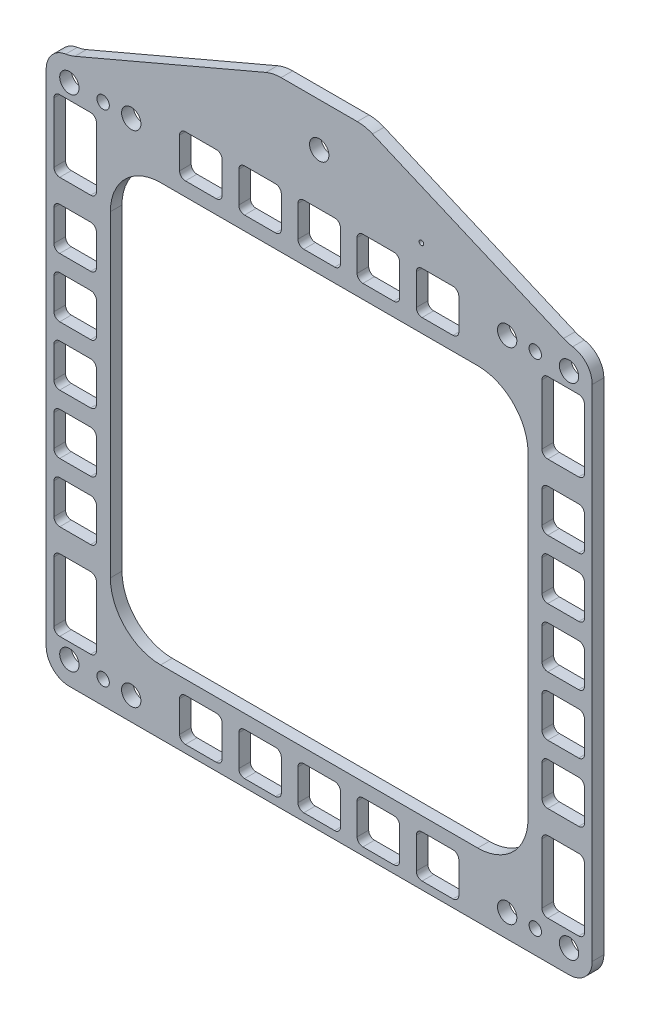
SolidWorks part; units mm, degrees
ref_plane "Front Plane" through (0, 0, 0) normal (0, 0, 1) x (1, 0, 0)
ref_plane "Top Plane" through (0, 0, 0) normal (0, 1, 0) x (1, 0, 0)
ref_plane "Right Plane" through (0, 0, 0) normal (1, 0, 0) x (0, 0, -1)
sketch "Sketch1" plane through (0, 0, 0) normal (0, 0, 1) x (1, 0, 0)
  point P0 (0, 54)
  point P1 (-54, 0)
  line B0 (-70.6, -64.6) -> (-70.6, 64.6)
  line B1 (-57.6, 43.65) -> (-57.6, 59.15)
  line B2 (-36.1, 67.1) -> (-36.1, 59.1)
  line B3 (-63.1825, 71.2052) -> (-13.7811, 92.2969)
  circle B4 centre (26.429, 74.25) radius 0.6
  circle B5 centre (0, 81.85) radius 2.5
  line B6 (-67.1, -60.65) -> (-59.1, -60.65)
  arc B7 (-68.6, -59.15) -> (-67.1, -60.65) centre (-67.1, -59.15) ccw
  line B8 (-68.6, -43.65) -> (-68.6, -59.15)
  arc B9 (-67.1, -42.15) -> (-68.6, -43.65) centre (-67.1, -43.65) ccw
  line B10 (-59.1, -42.15) -> (-67.1, -42.15)
  arc B11 (-57.6, -43.65) -> (-59.1, -42.15) centre (-59.1, -43.65) ccw
  line B12 (-57.6, -59.15) -> (-57.6, -43.65)
  arc B13 (-59.1, -60.65) -> (-57.6, -59.15) centre (-59.1, -59.15) ccw
  line B14 (67.1, -42.15) -> (59.1, -42.15)
  arc B15 (68.6, -43.65) -> (67.1, -42.15) centre (67.1, -43.65) ccw
  line B16 (68.6, -59.15) -> (68.6, -43.65)
  arc B17 (67.1, -60.65) -> (68.6, -59.15) centre (67.1, -59.15) ccw
  line B18 (59.1, -60.65) -> (67.1, -60.65)
  arc B19 (57.6, -59.15) -> (59.1, -60.65) centre (59.1, -59.15) ccw
  line B20 (57.6, -43.65) -> (57.6, -59.15)
  arc B21 (59.1, -42.15) -> (57.6, -43.65) centre (59.1, -43.65) ccw
  line B22 (67.1, 60.65) -> (59.1, 60.65)
  arc B23 (68.6, 59.15) -> (67.1, 60.65) centre (67.1, 59.15) ccw
  line B24 (68.6, 43.65) -> (68.6, 59.15)
  arc B25 (67.1, 42.15) -> (68.6, 43.65) centre (67.1, 43.65) ccw
  line B26 (59.1, 42.15) -> (67.1, 42.15)
  arc B27 (57.6, 43.65) -> (59.1, 42.15) centre (59.1, 43.65) ccw
  line B28 (57.6, 59.15) -> (57.6, 43.65)
  arc B29 (59.1, 60.65) -> (57.6, 59.15) centre (59.1, 59.15) ccw
  line B30 (-67.1, 42.15) -> (-59.1, 42.15)
  arc B31 (-68.6, 43.65) -> (-67.1, 42.15) centre (-67.1, 43.65) ccw
  line B32 (-68.6, 59.15) -> (-68.6, 43.65)
  arc B33 (-67.1, 60.65) -> (-68.6, 59.15) centre (-67.1, 59.15) ccw
  line B34 (-59.1, 60.65) -> (-67.1, 60.65)
  arc B35 (-57.6, 59.15) -> (-59.1, 60.65) centre (-59.1, 59.15) ccw
  arc B36 (-59.1, 42.15) -> (-57.6, 43.65) centre (-59.1, 43.65) ccw
  line B37 (68.6, 26.6) -> (68.6, 34.6)
  arc B38 (68.6, 34.6) -> (67.1, 36.1) centre (67.1, 34.6) ccw
  line B39 (67.1, 36.1) -> (59.1, 36.1)
  arc B40 (59.1, 36.1) -> (57.6, 34.6) centre (59.1, 34.6) ccw
  line B41 (57.6, 26.6) -> (57.6, 34.6)
  arc B42 (57.6, 26.6) -> (59.1, 25.1) centre (59.1, 26.6) ccw
  line B43 (67.1, 25.1) -> (59.1, 25.1)
  arc B44 (67.1, 25.1) -> (68.6, 26.6) centre (67.1, 26.6) ccw
  line B45 (68.6, 11.3) -> (68.6, 19.3)
  arc B46 (68.6, 19.3) -> (67.1, 20.8) centre (67.1, 19.3) ccw
  line B47 (67.1, 20.8) -> (59.1, 20.8)
  arc B48 (59.1, 20.8) -> (57.6, 19.3) centre (59.1, 19.3) ccw
  line B49 (57.6, 11.3) -> (57.6, 19.3)
  arc B50 (57.6, 11.3) -> (59.1, 9.8) centre (59.1, 11.3) ccw
  line B51 (67.1, 9.8) -> (59.1, 9.8)
  arc B52 (67.1, 9.8) -> (68.6, 11.3) centre (67.1, 11.3) ccw
  line B53 (68.6, -4) -> (68.6, 4)
  arc B54 (68.6, 4) -> (67.1, 5.5) centre (67.1, 4) ccw
  line B55 (67.1, 5.5) -> (59.1, 5.5)
  arc B56 (59.1, 5.5) -> (57.6, 4) centre (59.1, 4) ccw
  line B57 (57.6, -4) -> (57.6, 4)
  arc B58 (57.6, -4) -> (59.1, -5.5) centre (59.1, -4) ccw
  line B59 (67.1, -5.5) -> (59.1, -5.5)
  arc B60 (67.1, -5.5) -> (68.6, -4) centre (67.1, -4) ccw
  line B61 (68.6, -19.3) -> (68.6, -11.3)
  arc B62 (68.6, -11.3) -> (67.1, -9.8) centre (67.1, -11.3) ccw
  line B63 (67.1, -9.8) -> (59.1, -9.8)
  arc B64 (59.1, -9.8) -> (57.6, -11.3) centre (59.1, -11.3) ccw
  line B65 (57.6, -19.3) -> (57.6, -11.3)
  arc B66 (57.6, -19.3) -> (59.1, -20.8) centre (59.1, -19.3) ccw
  line B67 (67.1, -20.8) -> (59.1, -20.8)
  arc B68 (67.1, -20.8) -> (68.6, -19.3) centre (67.1, -19.3) ccw
  line B69 (68.6, -34.6) -> (68.6, -26.6)
  arc B70 (68.6, -26.6) -> (67.1, -25.1) centre (67.1, -26.6) ccw
  line B71 (67.1, -25.1) -> (59.1, -25.1)
  arc B72 (59.1, -25.1) -> (57.6, -26.6) centre (59.1, -26.6) ccw
  line B73 (57.6, -34.6) -> (57.6, -26.6)
  arc B74 (57.6, -34.6) -> (59.1, -36.1) centre (59.1, -34.6) ccw
  line B75 (67.1, -36.1) -> (59.1, -36.1)
  arc B76 (67.1, -36.1) -> (68.6, -34.6) centre (67.1, -34.6) ccw
  line B77 (26.6, -68.6) -> (34.6, -68.6)
  arc B78 (34.6, -68.6) -> (36.1, -67.1) centre (34.6, -67.1) ccw
  line B79 (36.1, -67.1) -> (36.1, -59.1)
  arc B80 (36.1, -59.1) -> (34.6, -57.6) centre (34.6, -59.1) ccw
  line B81 (26.6, -57.6) -> (34.6, -57.6)
  arc B82 (26.6, -57.6) -> (25.1, -59.1) centre (26.6, -59.1) ccw
  line B83 (25.1, -67.1) -> (25.1, -59.1)
  arc B84 (25.1, -67.1) -> (26.6, -68.6) centre (26.6, -67.1) ccw
  line B85 (11.3, -68.6) -> (19.3, -68.6)
  arc B86 (19.3, -68.6) -> (20.8, -67.1) centre (19.3, -67.1) ccw
  line B87 (20.8, -67.1) -> (20.8, -59.1)
  arc B88 (20.8, -59.1) -> (19.3, -57.6) centre (19.3, -59.1) ccw
  line B89 (11.3, -57.6) -> (19.3, -57.6)
  arc B90 (11.3, -57.6) -> (9.8, -59.1) centre (11.3, -59.1) ccw
  line B91 (9.8, -67.1) -> (9.8, -59.1)
  arc B92 (9.8, -67.1) -> (11.3, -68.6) centre (11.3, -67.1) ccw
  line B93 (-4, -68.6) -> (4, -68.6)
  arc B94 (4, -68.6) -> (5.5, -67.1) centre (4, -67.1) ccw
  line B95 (5.5, -67.1) -> (5.5, -59.1)
  arc B96 (5.5, -59.1) -> (4, -57.6) centre (4, -59.1) ccw
  line B97 (-4, -57.6) -> (4, -57.6)
  arc B98 (-4, -57.6) -> (-5.5, -59.1) centre (-4, -59.1) ccw
  line B99 (-5.5, -67.1) -> (-5.5, -59.1)
  arc B100 (-5.5, -67.1) -> (-4, -68.6) centre (-4, -67.1) ccw
  line B101 (-19.3, -68.6) -> (-11.3, -68.6)
  arc B102 (-11.3, -68.6) -> (-9.8, -67.1) centre (-11.3, -67.1) ccw
  line B103 (-9.8, -67.1) -> (-9.8, -59.1)
  arc B104 (-9.8, -59.1) -> (-11.3, -57.6) centre (-11.3, -59.1) ccw
  line B105 (-19.3, -57.6) -> (-11.3, -57.6)
  arc B106 (-19.3, -57.6) -> (-20.8, -59.1) centre (-19.3, -59.1) ccw
  line B107 (-20.8, -67.1) -> (-20.8, -59.1)
  arc B108 (-20.8, -67.1) -> (-19.3, -68.6) centre (-19.3, -67.1) ccw
  line B109 (-34.6, -68.6) -> (-26.6, -68.6)
  arc B110 (-26.6, -68.6) -> (-25.1, -67.1) centre (-26.6, -67.1) ccw
  line B111 (-25.1, -67.1) -> (-25.1, -59.1)
  arc B112 (-25.1, -59.1) -> (-26.6, -57.6) centre (-26.6, -59.1) ccw
  line B113 (-34.6, -57.6) -> (-26.6, -57.6)
  arc B114 (-34.6, -57.6) -> (-36.1, -59.1) centre (-34.6, -59.1) ccw
  line B115 (-36.1, -67.1) -> (-36.1, -59.1)
  arc B116 (-36.1, -67.1) -> (-34.6, -68.6) centre (-34.6, -67.1) ccw
  circle B117 centre (48.6, -64.6) radius 2.5
  circle B118 centre (64.6, -64.6) radius 2.5
  circle B119 centre (64.6, 64.6) radius 2.5
  circle B120 centre (-48.6, 64.6) radius 2.5
  circle B121 centre (48.6, 64.6) radius 2.5
  circle B122 centre (-48.6, -64.6) radius 2.5
  circle B123 centre (-64.6, -64.6) radius 2.5
  circle B124 centre (-64.6, 64.6) radius 2.5
  line B125 (-41, 54) -> (41, 54)
  arc B126 (54, 41) -> (41, 54) centre (41, 41) ccw
  line B127 (54, -41) -> (54, 41)
  arc B128 (41, -54) -> (54, -41) centre (41, -41) ccw
  line B129 (-41, -54) -> (41, -54)
  arc B130 (-54, -41) -> (-41, -54) centre (-41, -41) ccw
  line B131 (-54, -41) -> (-54, 41)
  arc B132 (-41, 54) -> (-54, 41) centre (-41, 41) ccw
  line B133 (-9.8546, 93.1) -> (9.8546, 93.1)
  arc B134 (13.7811, 92.2969) -> (9.8546, 93.1) centre (9.8546, 83.1) ccw
  line B135 (13.7811, 92.2969) -> (63.1825, 71.2052)
  arc B136 (63.1825, 71.2052) -> (65.5409, 70.5258) centre (67.1091, 80.402) ccw
  arc B137 (70.6, 64.6) -> (65.5409, 70.5258) centre (64.6, 64.6) ccw
  line B138 (70.6, -64.6) -> (70.6, 64.6)
  arc B139 (64.6, -70.6) -> (70.6, -64.6) centre (64.6, -64.6) ccw
  line B140 (-64.6, -70.6) -> (64.6, -70.6)
  arc B141 (-70.6, -64.6) -> (-64.6, -70.6) centre (-64.6, -64.6) ccw
  arc B142 (-65.5409, 70.5258) -> (-70.6, 64.6) centre (-64.6, 64.6) ccw
  arc B143 (-65.5409, 70.5258) -> (-63.1825, 71.2052) centre (-67.1091, 80.402) ccw
  arc B144 (-9.8546, 93.1) -> (-13.7811, 92.2969) centre (-9.8546, 83.1) ccw
  line B145 (-67.1, 25.1) -> (-59.1, 25.1)
  arc B146 (-59.1, 25.1) -> (-57.6, 26.6) centre (-59.1, 26.6) ccw
  line B147 (-57.6, 26.6) -> (-57.6, 34.6)
  arc B148 (-57.6, 34.6) -> (-59.1, 36.1) centre (-59.1, 34.6) ccw
  line B149 (-67.1, 36.1) -> (-59.1, 36.1)
  arc B150 (-67.1, 36.1) -> (-68.6, 34.6) centre (-67.1, 34.6) ccw
  line B151 (-68.6, 26.6) -> (-68.6, 34.6)
  arc B152 (-68.6, 26.6) -> (-67.1, 25.1) centre (-67.1, 26.6) ccw
  arc B153 (-36.1, 59.1) -> (-34.6, 57.6) centre (-34.6, 59.1) ccw
  line B154 (-34.6, 57.6) -> (-26.6, 57.6)
  arc B155 (-26.6, 57.6) -> (-25.1, 59.1) centre (-26.6, 59.1) ccw
  line B156 (-25.1, 67.1) -> (-25.1, 59.1)
  arc B157 (-25.1, 67.1) -> (-26.6, 68.6) centre (-26.6, 67.1) ccw
  line B158 (-34.6, 68.6) -> (-26.6, 68.6)
  arc B159 (-34.6, 68.6) -> (-36.1, 67.1) centre (-34.6, 67.1) ccw
  line B160 (-20.8, 67.1) -> (-20.8, 59.1)
  arc B161 (-20.8, 59.1) -> (-19.3, 57.6) centre (-19.3, 59.1) ccw
  line B162 (-19.3, 57.6) -> (-11.3, 57.6)
  arc B163 (-11.3, 57.6) -> (-9.8, 59.1) centre (-11.3, 59.1) ccw
  line B164 (-9.8, 67.1) -> (-9.8, 59.1)
  arc B165 (-9.8, 67.1) -> (-11.3, 68.6) centre (-11.3, 67.1) ccw
  line B166 (-19.3, 68.6) -> (-11.3, 68.6)
  arc B167 (-19.3, 68.6) -> (-20.8, 67.1) centre (-19.3, 67.1) ccw
  line B168 (-5.5, 67.1) -> (-5.5, 59.1)
  arc B169 (-5.5, 59.1) -> (-4, 57.6) centre (-4, 59.1) ccw
  line B170 (-4, 57.6) -> (4, 57.6)
  arc B171 (4, 57.6) -> (5.5, 59.1) centre (4, 59.1) ccw
  line B172 (5.5, 67.1) -> (5.5, 59.1)
  arc B173 (5.5, 67.1) -> (4, 68.6) centre (4, 67.1) ccw
  line B174 (-4, 68.6) -> (4, 68.6)
  arc B175 (-4, 68.6) -> (-5.5, 67.1) centre (-4, 67.1) ccw
  line B176 (-67.1, 9.8) -> (-59.1, 9.8)
  arc B177 (-59.1, 9.8) -> (-57.6, 11.3) centre (-59.1, 11.3) ccw
  line B178 (-57.6, 11.3) -> (-57.6, 19.3)
  arc B179 (-57.6, 19.3) -> (-59.1, 20.8) centre (-59.1, 19.3) ccw
  line B180 (-67.1, 20.8) -> (-59.1, 20.8)
  arc B181 (-67.1, 20.8) -> (-68.6, 19.3) centre (-67.1, 19.3) ccw
  line B182 (-68.6, 11.3) -> (-68.6, 19.3)
  arc B183 (-68.6, 11.3) -> (-67.1, 9.8) centre (-67.1, 11.3) ccw
  line B184 (-67.1, -5.5) -> (-59.1, -5.5)
  arc B185 (-59.1, -5.5) -> (-57.6, -4) centre (-59.1, -4) ccw
  line B186 (-57.6, -4) -> (-57.6, 4)
  arc B187 (-57.6, 4) -> (-59.1, 5.5) centre (-59.1, 4) ccw
  line B188 (-67.1, 5.5) -> (-59.1, 5.5)
  arc B189 (-67.1, 5.5) -> (-68.6, 4) centre (-67.1, 4) ccw
  line B190 (-68.6, -4) -> (-68.6, 4)
  arc B191 (-68.6, -4) -> (-67.1, -5.5) centre (-67.1, -4) ccw
  line B192 (-67.1, -20.8) -> (-59.1, -20.8)
  arc B193 (-59.1, -20.8) -> (-57.6, -19.3) centre (-59.1, -19.3) ccw
  line B194 (-57.6, -19.3) -> (-57.6, -11.3)
  arc B195 (-57.6, -11.3) -> (-59.1, -9.8) centre (-59.1, -11.3) ccw
  line B196 (-67.1, -9.8) -> (-59.1, -9.8)
  arc B197 (-67.1, -9.8) -> (-68.6, -11.3) centre (-67.1, -11.3) ccw
  line B198 (-68.6, -19.3) -> (-68.6, -11.3)
  arc B199 (-68.6, -19.3) -> (-67.1, -20.8) centre (-67.1, -19.3) ccw
  line B200 (-67.1, -36.1) -> (-59.1, -36.1)
  arc B201 (-59.1, -36.1) -> (-57.6, -34.6) centre (-59.1, -34.6) ccw
  line B202 (-57.6, -34.6) -> (-57.6, -26.6)
  arc B203 (-57.6, -26.6) -> (-59.1, -25.1) centre (-59.1, -26.6) ccw
  line B204 (-67.1, -25.1) -> (-59.1, -25.1)
  arc B205 (-67.1, -25.1) -> (-68.6, -26.6) centre (-67.1, -26.6) ccw
  line B206 (-68.6, -34.6) -> (-68.6, -26.6)
  arc B207 (-68.6, -34.6) -> (-67.1, -36.1) centre (-67.1, -34.6) ccw
  line B208 (25.1, 67.1) -> (25.1, 59.1)
  arc B209 (25.1, 59.1) -> (26.6, 57.6) centre (26.6, 59.1) ccw
  line B210 (26.6, 57.6) -> (34.6, 57.6)
  arc B211 (34.6, 57.6) -> (36.1, 59.1) centre (34.6, 59.1) ccw
  line B212 (36.1, 67.1) -> (36.1, 59.1)
  arc B213 (36.1, 67.1) -> (34.6, 68.6) centre (34.6, 67.1) ccw
  line B214 (26.6, 68.6) -> (34.6, 68.6)
  arc B215 (26.6, 68.6) -> (25.1, 67.1) centre (26.6, 67.1) ccw
  line B216 (9.8, 67.1) -> (9.8, 59.1)
  arc B217 (9.8, 59.1) -> (11.3, 57.6) centre (11.3, 59.1) ccw
  line B218 (11.3, 57.6) -> (19.3, 57.6)
  arc B219 (19.3, 57.6) -> (20.8, 59.1) centre (19.3, 59.1) ccw
  line B220 (20.8, 67.1) -> (20.8, 59.1)
  arc B221 (20.8, 67.1) -> (19.3, 68.6) centre (19.3, 67.1) ccw
  line B222 (11.3, 68.6) -> (19.3, 68.6)
  arc B223 (11.3, 68.6) -> (9.8, 67.1) centre (11.3, 67.1) ccw
  circle B224 centre (-55.87, 64.6) radius 1.6
  circle B225 centre (55.87, 64.6) radius 1.6
  circle B226 centre (55.87, -64.6) radius 1.6
  circle B227 centre (-55.87, -64.6) radius 1.6
sketch_block_instance "Layer3-1"
sketch_block "Layer3"
extrude "Boss-Extrude1" add sketch "Sketch1" along normal blind 3
